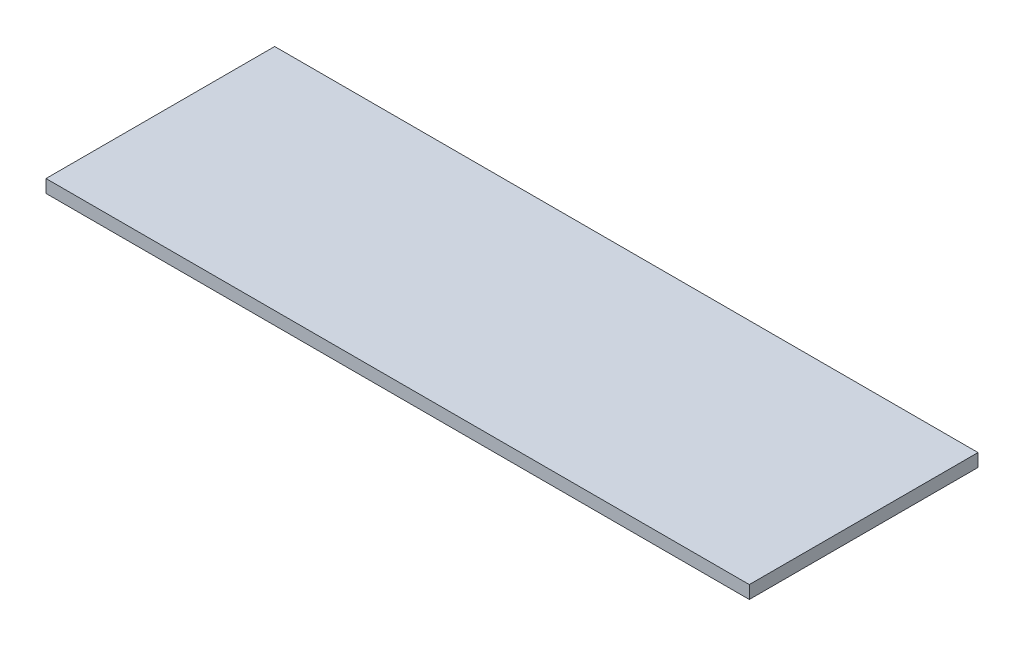
SolidWorks part; units mm, degrees
ref_plane "Front Plane" through (0, 0, 0) normal (0, 0, 1) x (1, 0, 0)
ref_plane "Top Plane" through (0, 0, 0) normal (0, 1, 0) x (1, 0, 0)
ref_plane "Right Plane" through (0, 0, 0) normal (1, 0, 0) x (0, 0, -1)
sketch "Sketch2" plane through (0, 0, 0) normal (0, 1, 0) x (1, 0, 0)
  line L1 (163, -53) -> (-163, -53)
  line L2 (163, -53) -> (163, 53)
  line L3 (163, 53) -> (-163, 53)
  line L4 (-163, -53) -> (-163, 53)
  line L5 (163, -53) -> (-163, 53) construction
  line L6 (163, 53) -> (-163, -53) construction
  point P0 (0, 0)
  dimension "D1" = 106
  dimension "D2" = 326
extrude "Boss-Extrude1" add sketch "Sketch2" along normal blind 6
sketch "Sketch3" plane through (0, 6, 0) normal (0, 1, 0) x (1, 0, 0)
  line L0 (-163, 50) -> (163, 50) construction
  line L1 (-163, 53) -> (-163, -53) construction
  line L2 (-163, -53) -> (163, -53) construction
  circle A0 centre (-143, 35) radius 4
  circle A1 centre (-143, 2) radius 4
  circle A2 centre (-103, 35) radius 4
  circle A3 centre (-103, 2) radius 4
  dimension "D1" = 8
  dimension "D2" = 8
  dimension "D3" = 8
  dimension "D4" = 8
  dimension "D5" = 15
  dimension "D6" = 20
  dimension "D7" = 55
  dimension "D8" = 20
  dimension "D9" = 15
  dimension "D10" = 40
  dimension "D11" = 55
  dimension "D12" = 40
sketch "Sketch4" plane through (0, 6, 0) normal (0, 1, 0) x (1, 0, 0)
  line L0 (-163, 50) -> (163, 50) construction
  line L1 (163, -53) -> (163, 53) construction
  line L2 (-163, -53) -> (163, -53) construction
  circle A0 centre (151, 35) radius 4
  circle A1 centre (134, 35) radius 4
  circle A2 centre (151, 2) radius 4
  circle A3 centre (134, 2) radius 4
  dimension "D1" = 15
  dimension "D2" = 8
  dimension "D3" = 8
  dimension "D4" = 8
  dimension "D5" = 8
  dimension "D6" = 12
  dimension "D7" = 12
  dimension "D8" = 55
  dimension "D9" = 55
  dimension "D10" = 15
  dimension "D11" = 17
  dimension "D12" = 17
